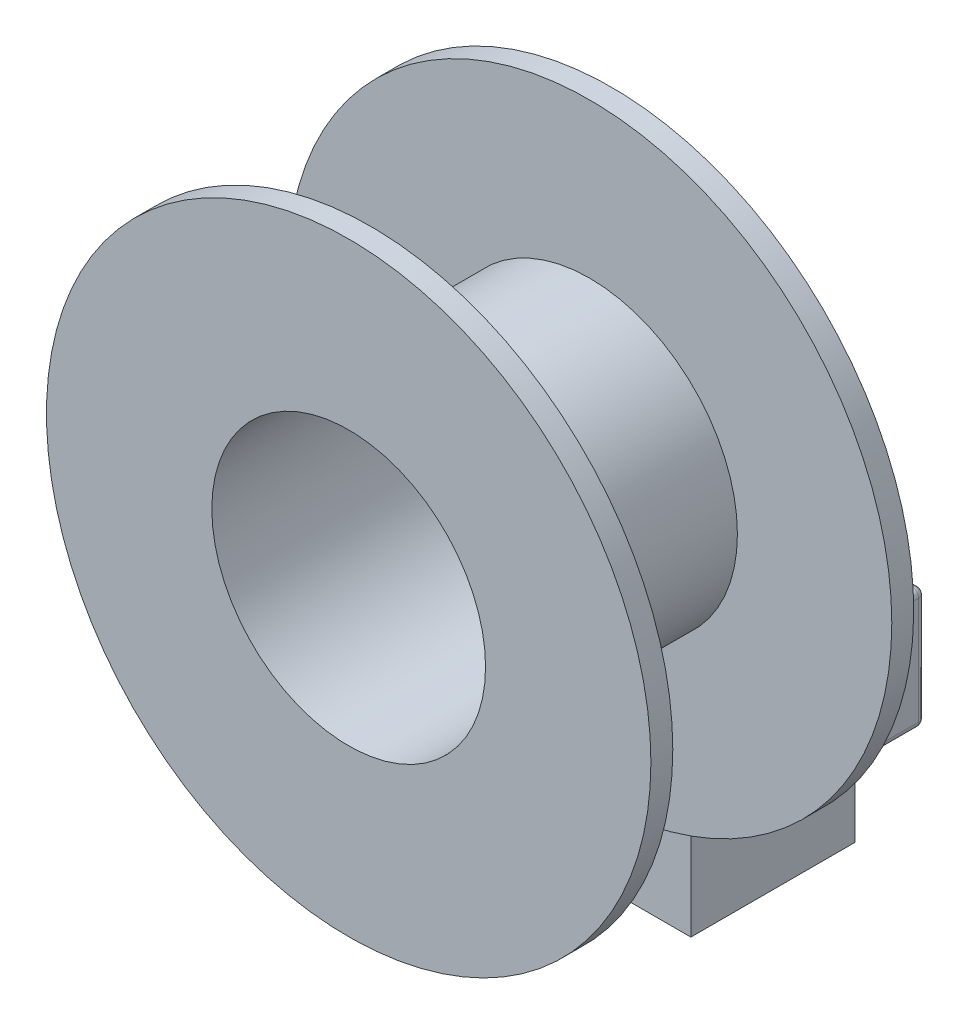
SolidWorks part; units mm, degrees
material "ABS"
ref_plane "Спереди" through (0, 0, 0) normal (0, 0, 1) x (1, 0, 0)
ref_plane "Сверху" through (0, 0, 0) normal (0, 1, 0) x (1, 0, 0)
ref_plane "Справа" through (0, 0, 0) normal (1, 0, 0) x (0, 0, -1)
sketch "Эскиз1" plane through (0, 0, 0) normal (0, 0, 1) x (1, 0, 0)
  circle A0 centre (0, 0) radius 13.8
  circle A1 centre (0, 0) radius 6.25
extrude "Бобышка-Вытянуть1" add sketch "Эскиз1" along normal blind 1
sketch "Эскиз2" plane through (0, 0, 1) normal (0, 0, 1) x (1, 0, 0)
  circle A0 centre (0, 0) radius 6.25
  circle A1 centre (0, 0) radius 6.75
extrude "Бобышка-Вытянуть2" add sketch "Эскиз2" along normal blind 10
sketch "Эскиз3" plane through (0, 0, 11) normal (0, 0, 1) x (1, 0, 0)
  circle A0 centre (0, 0) radius 6.25
  circle A1 centre (0, 0) radius 13.8
extrude "Бобышка-Вытянуть3" add sketch "Эскиз3" along normal blind 1
sketch "Эскиз4" plane through (0, 0, 0) normal (0, 0, -1) x (-1, 0, 0)
  line L0 (0, 0) -> (0, -13.8) construction
  line L1 (-4.125, -9) -> (4.125, -9)
  line L2 (-4.125, -17.5) -> (4.125, -17.5)
  line L3 (4.125, -17.5) -> (4.125, -9)
  line L4 (-4.125, -9) -> (-4.125, -17.5)
  circle A0 centre (0, 0) radius 13.8 construction
  point P7 (0, -9)
extrude "Бобышка-Вытянуть4" add sketch "Эскиз4" along normal blind 7 and the other way blind 0.5
sketch "Эскиз5" plane through (0, 0, -7) normal (0, 0, -1) x (-1, 0, 0)
  line L0 (4.125, -17.5) -> (4.125, -9) construction
  line L1 (-4.125, -9) -> (4.125, -9)
  line L2 (-4.125, -9) -> (-4.125, -14.5)
  line L3 (-4.125, -14.5) -> (4.125, -14.5)
  line L4 (4.125, -9) -> (4.125, -14.5)
  line L5 (4.125, -9) -> (4.125, -13.1691) construction
extrude "Бобышка-Вытянуть5" add sketch "Эскиз5" along normal blind 3.2
fillet "Скругление1" radius 0.3 8 edges at (-4.125, -9, -5.1) (-4.125, -14.5, -8.6) (4.125, -14.5, -8.6) (0, -14.5, -10.2) (4.125, -11.75, -10.2) (-4.125, -11.75, -10.2) (0, -9, -10.2) (4.125, -9, -5.1)
